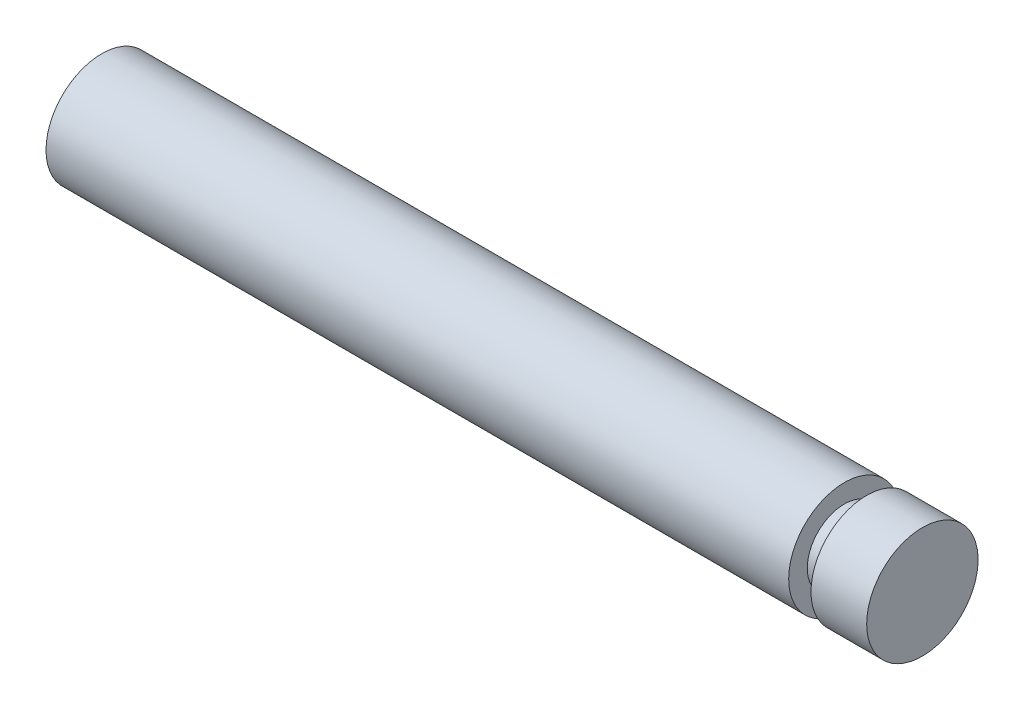
SolidWorks part; units mm, degrees
ref_plane "Front Plane" through (0, 0, 0) normal (0, 0, 1) x (1, 0, 0)
ref_plane "Top Plane" through (0, 0, 0) normal (0, 1, 0) x (1, 0, 0)
ref_plane "Right Plane" through (0, 0, 0) normal (1, 0, 0) x (0, 0, -1)
sketch "Sketch1" plane through (0, 0, 0) normal (0, 0, 1) x (1, 0, 0)
  line L0 (0, 0) -> (44.1915, 0) construction
  line L1 (0, 0) -> (0, 3)
  line L2 (0, 3) -> (39.9915, 3)
  line L3 (39.9915, 3) -> (39.9915, 2)
  line L4 (39.9915, 2) -> (41.1915, 2)
  line L5 (41.1915, 2) -> (41.1915, 3)
  line L6 (41.1915, 3) -> (44.1915, 3)
  line L7 (44.1915, 3) -> (44.1915, 0)
  line L8 (0, 0) -> (44.1915, 0)
  dimension "D1" = 39.9915
  dimension "D2" = 1.2
  dimension "D3" = 3
  dimension "D4" = 6
  dimension "D5" = 4
revolve "Revolve1" add sketch "Sketch1" angle 360 about L0
